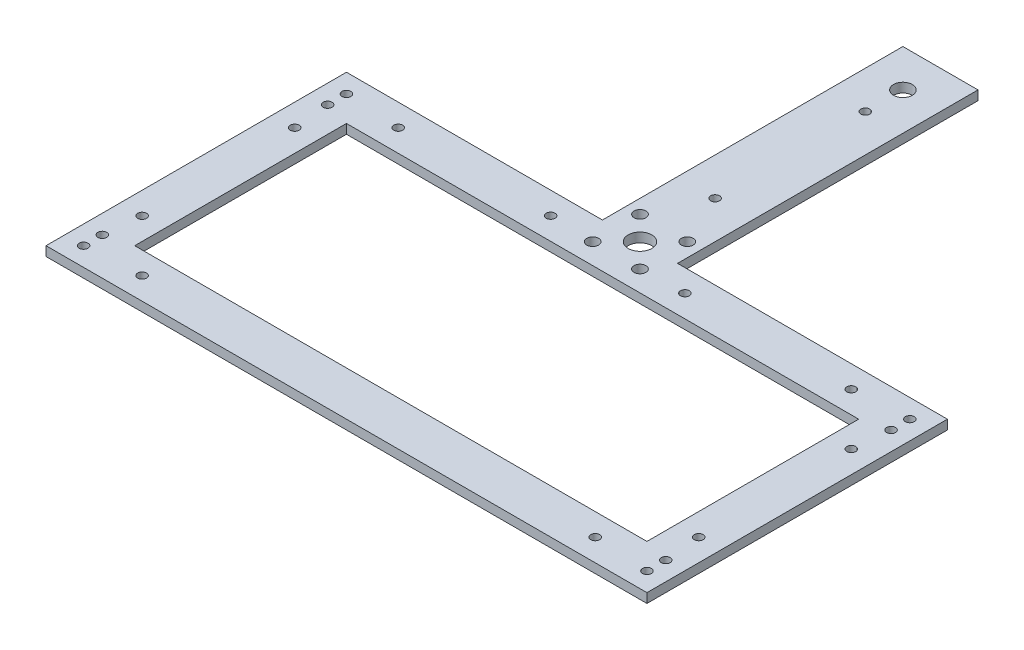
SolidWorks part; units mm, degrees
ref_plane "Front" through (0, 0, 0) normal (0, 0, 1) x (1, 0, 0)
ref_plane "Top" through (0, 0, 0) normal (0, 1, 0) x (1, 0, 0)
ref_plane "Right" through (0, 0, 0) normal (1, 0, 0) x (0, 0, -1)
sketch "Sketch1" plane through (0, 0, 0) normal (0, 1, 0) x (1, 0, 0)
  line L0 (6.35, 101.6) -> (6.35, 95.25)
  line L1 (0, 0) -> (203.2, 0)
  line L2 (0, 0) -> (0, 101.6)
  line L3 (0, 101.6) -> (203.2, 101.6)
  line L4 (203.2, 0) -> (203.2, 101.6)
  line L5 (15, 86.6) -> (188.2, 86.6)
  line L6 (15, 86.6) -> (15, 15)
  line L7 (15, 15) -> (188.2, 15)
  line L8 (188.2, 86.6) -> (188.2, 15)
  line L9 (6.35, 95.25) -> (6.35, 88.9)
  line L10 (15, 50.8) -> (2.3, 50.8)
  line L11 (101.6, 15) -> (101.6, 2.3)
  line L13 (86.5462, 101.6) -> (111.9462, 101.6)
  line L14 (86.5462, 101.6) -> (86.5462, 203.2)
  line L15 (86.5462, 203.2) -> (111.9462, 203.2)
  line L16 (111.9462, 101.6) -> (111.9462, 203.2)
  circle A0 centre (6.35, 95.25) radius 1.5
  circle A1 centre (6.35, 88.9) radius 1.5
  circle A2 centre (6.35, 6.35) radius 1.5
  circle A3 centre (6.35, 12.7) radius 1.5
  circle A4 centre (196.85, 95.25) radius 1.5
  circle A5 centre (196.85, 88.9) radius 1.5
  circle A6 centre (196.85, 12.7) radius 1.5
  circle A7 centre (196.85, 6.35) radius 1.5
  dimension "D10" = 25.4
  dimension "D1" = 101.6
  dimension "D2" = 203.2
  dimension "D3" = 15
  dimension "D4" = 15
  dimension "D5" = 15
  dimension "D6" = 15
  dimension "D7" = 6.35
  dimension "D8" = 6.35
  dimension "D9" = 6.35
  dimension "D11" = 101.6
extrude "Boss-Extrude1" add sketch "Sketch1" along normal blind 3.175
sketch "Sketch2" plane through (0, 3.175, 0) normal (0, 1, 0) x (1, 0, 0)
  line L0 (86.5462, 101.6) -> (111.9462, 101.6)
  line L1 (91.2462, 93.6) -> (107.2462, 109.6)
  line L2 (91.2462, 109.6) -> (107.2462, 93.6)
  circle A0 centre (99.2462, 101.6) radius 11.3137
  circle A1 centre (91.2462, 109.6) radius 2
  circle A2 centre (107.2462, 109.6) radius 2
  circle A3 centre (91.2462, 93.6) radius 2
  circle A4 centre (107.2462, 93.6) radius 2
  circle A5 centre (99.2462, 101.6) radius 4
  point P9 (99.2462, 101.6)
  point P12 (99.2462, 101.6)
extrude "Cut-Extrude1" cut sketch "Sketch2" against normal blind 3.175 contours A0 A2 | L1 A2 A0 | A0 A2 L1 | A1 | A3 | A4 | A5
sketch "Sketch3" plane through (0, 3.175, 0) normal (0, 1, 0) x (1, 0, 0)
  line L0 (188.2, 86.6) -> (188.2, 101.6)
  line L1 (111.9462, 101.6) -> (203.2, 101.6) construction
  line L2 (188.2, 101.6) -> (188.2, 86.6)
  line L3 (203.2, 86.6) -> (188.2, 86.6)
  line L4 (203.2, 0) -> (203.2, 101.6) construction
  line L5 (188.2, 15) -> (203.2, 15)
  line L6 (203.2, 15) -> (188.2, 15)
  line L7 (188.2, 0) -> (188.2, 15)
  line L8 (0, 0) -> (203.2, 0) construction
  line L9 (15, 86.6) -> (0, 86.6)
  line L10 (0, 0) -> (0, 101.6) construction
  line L11 (195.7, 86.6) -> (195.7, 15)
  line L12 (188.2, 7.5) -> (15, 7.5)
  line L13 (7.5, 86.6) -> (7.5, 15)
  line L14 (188.2, 94.1) -> (15, 94.1)
  line L15 (111.9462, 101.6) -> (111.9462, 203.2) construction
  line L16 (86.5462, 101.6) -> (86.5462, 203.2) construction
  circle A0 centre (178.2, 94.1) radius 1.5
  circle A1 centre (25, 94.1) radius 1.5
  circle A2 centre (76.5462, 94.1) radius 1.5
  circle A3 centre (121.9462, 94.1) radius 1.5
  circle A4 centre (178.2, 7.5) radius 1.5
  circle A5 centre (25, 7.5) radius 1.5
  circle A6 centre (195.7, 76.6) radius 1.5
  circle A8 centre (195.7, 25) radius 1.5
  circle A9 centre (7.5, 76.6) radius 1.5
  circle A10 centre (7.5, 25) radius 1.5
  dimension "D1" = 10
  dimension "D5" = 10
  dimension "D2" = 10
  dimension "D3" = 10
  dimension "D4" = 10
  dimension "D6" = 10
  dimension "D7" = 10
  dimension "D8" = 10
extrude "Cut-Extrude2" cut sketch "Sketch3" against normal blind 10 contours A0 | A3 | A2 | A1 | A9 | A5 | A10 | A4 | A8 | A6
sketch "Sketch4" plane through (0, 3.175, 0) normal (0, 1, 0) x (1, 0, 0)
  line L0 (99.2462, 203.2) -> (99.2462, 190.5)
  line L1 (86.5462, 203.2) -> (111.9462, 203.2) construction
  circle A0 centre (99.2462, 190.5) radius 3.175
sketch "Sketch5" plane through (0, 3.175, 0) normal (0, 1, 0) x (1, 0, 0)
  line L0 (99.2462, 101.6) -> (99.2462, 127)
  line L1 (99.2462, 127) -> (99.2462, 177.8)
  circle A0 centre (99.2462, 177.8) radius 1.5
  circle A1 centre (99.2462, 127) radius 1.5
  dimension "D1" = 25.4
  dimension "D2" = 50.8
extrude "Cut-Extrude3" cut sketch "Sketch4" against normal blind 10 contours A0
extrude "Cut-Extrude4" cut sketch "Sketch5" against normal blind 10 contours A0 | A1
